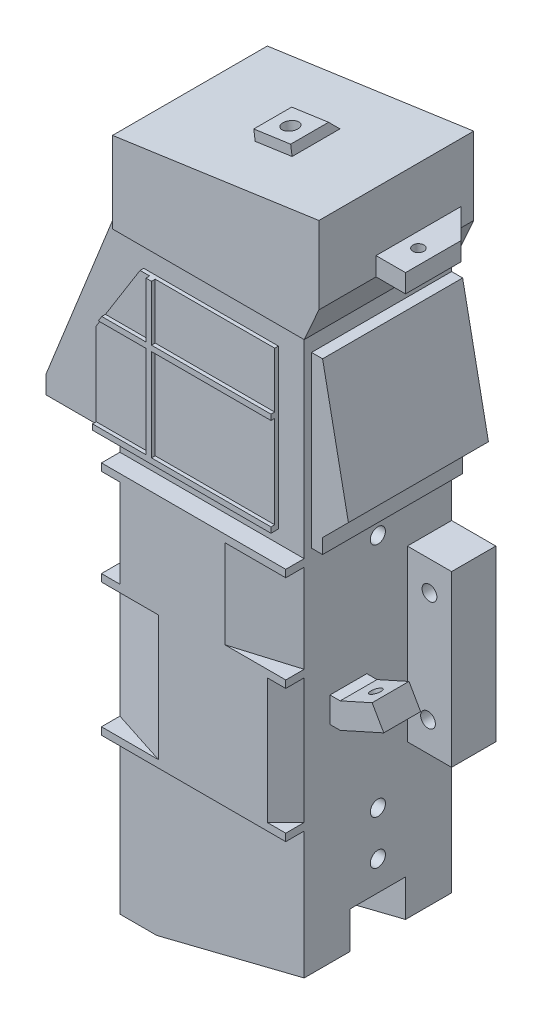
SolidWorks part; units mm, degrees
ref_plane "Alzado" through (0, 0, 0) normal (0, 0, 1) x (1, 0, 0)
ref_plane "Planta" through (0, 0, 0) normal (0, 1, 0) x (1, 0, 0)
ref_plane "Vista lateral" through (0, 0, 0) normal (1, 0, 0) x (0, 0, -1)
sketch "Croquis1" plane through (0, 0, 0) normal (0, 0, 1) x (1, 0, 0)
  line L1 (-25, -92) -> (25, -92)
  line L2 (-25, -92) -> (-25, 92)
  line L3 (-25, 92) -> (25, 92)
  line L4 (25, -92) -> (25, 92)
  line L5 (-25, -92) -> (25, 92) construction
  line L6 (-25, 92) -> (25, -92) construction
  point P0 (0, 0)
  dimension "D1" = 184
  dimension "D2" = 50
extrude "Saliente-Extruir1" add sketch "Croquis1" along normal blind 40
sketch "Croquis2" plane through (0, 0, 40) normal (0, 0, 1) x (1, 0, 0)
  line L0 (-25, -92) -> (-15, -92)
  line L1 (-25, -92) -> (25, -92) construction
  line L2 (-15, -92) -> (25, -82.0002)
  line L3 (25, -92) -> (25, 92) construction
  line L4 (25, -82.0002) -> (25, -92)
  line L5 (25, -92) -> (-15, -92)
  dimension "D1" = 10
  dimension "D2" = 41.231
extrude "Cortar-Extruir1" cut sketch "Croquis2" against normal blind 40 contours L2 L4 L5
sketch "Croquis3" plane through (0, 0, 40) normal (0, 0, 1) x (1, 0, 0)
  line L0 (25, -82.0002) -> (25, -40.5002)
  line L1 (25, -82.0002) -> (25, 92) construction
  line L2 (25, -40.5002) -> (17.2579, -40.5002)
  line L3 (25, -40.5002) -> (37, -40.5002)
  line L5 (23, 5.4998) -> (37, 5.4998)
  line L6 (37, -40.5002) -> (37, 5.4998)
  line L7 (17.2579, -40.5002) -> (17.2579, 5.4998)
  line L8 (17.2579, 5.4998) -> (23, 5.4998)
  circle A0 centre (30.6, -32.5002) radius 2
  circle A1 centre (31, -2.5002) radius 2
  line M8 (25, -82.0002) -> (25, 92)
  dimension "D4" = 4
  dimension "D7" = 8
  dimension "D1" = 41.5
  dimension "D2" = 12
  dimension "D3" = 46
  dimension "D5" = 6
  dimension "D6" = 30
extrude "Saliente-Extruir2" add sketch "Croquis3" against normal through all contours L3 L6 L5 A1 A0 M8 | L8 L7 L2 M8
sketch "Croquis4" plane through (0, 0, 40) normal (0, 0, 1) x (1, 0, 0)
  line L0 (25, 5.4998) -> (25, 17.9998)
  line L1 (25, 5.4998) -> (25, 92) construction
  line L2 (25, 17.9998) -> (28, 17.9998)
  line L3 (28, 17.9998) -> (28, 21.9998)
  line L4 (28, 21.9998) -> (34.9997, 28.9994)
  line L5 (34.9997, 28.9994) -> (27.9996, 63.9993)
  line L6 (27.9996, 63.9993) -> (25, 63.9993)
  line L7 (25, 63.9993) -> (25, 17.9998)
  line L8 (25, 63.9993) -> (25, 69.9993)
  line L9 (25, 69.9993) -> (27, 69.9993)
  line L10 (27, 69.9993) -> (31.0001, 78.9994)
  line L11 (31.0001, 78.9994) -> (42.3141, 78.9994)
  line L12 (42.3141, 78.9994) -> (42.3141, 83.9994)
  line L13 (42.3141, 83.9994) -> (31.0001, 83.9994)
  line L14 (25, 92) -> (31.0001, 92)
  line L15 (31.0001, 92) -> (31.0001, 83.9994)
  line L16 (25, 69.9993) -> (25, 92)
  dimension "D1" = 12.5
  dimension "D2" = 3
  dimension "D3" = 4
  dimension "D4" = 9.899
  dimension "D5" = 135
  dimension "D6" = 35.693
  dimension "D7" = 123.69
  dimension "D8" = 6
  dimension "D9" = 2
  dimension "D10" = 9.849
  dimension "D11" = 113.963
  dimension "D12" = 11.314
  dimension "D13" = 5
sketch "Croquis7" plane through (0, 0, 0) normal (0, 0, -1) x (-1, 0, 0)
  line L0 (-25, 17.9998) -> (-28, 17.9998)
  line L1 (-28, 17.9998) -> (-28, 21.9998)
  line L2 (-28, 21.9998) -> (-34.9997, 28.9994)
  line L3 (-34.9997, 28.9994) -> (-27.9996, 63.9993)
  line L4 (-27.9996, 63.9993) -> (-25, 63.9993)
  line L5 (-25, 63.9993) -> (-25, 17.9998)
extrude "Saliente-Extruir3" add sketch "Croquis7" against normal blind 38
sketch "Croquis8" plane through (0, 0, 0) normal (0, 0, -1) x (-1, 0, 0)
  line L0 (-25, 69.9993) -> (-27, 69.9993)
  line L1 (-27, 69.9993) -> (-31.0001, 78.9994)
  line L2 (-31.0001, 78.9994) -> (-42.3141, 78.9994)
  line L3 (-42.3141, 78.9994) -> (-42.3141, 83.9994)
  line L4 (-42.3141, 83.9994) -> (-31.0001, 83.9994)
  line L5 (-31.0001, 83.9994) -> (-31.0001, 92)
  line L6 (-31.0001, 92) -> (-25, 92)
  line L7 (-25, 92) -> (-25, 69.9993)
extrude "Saliente-Extruir4" add sketch "Croquis8" against normal through all
sketch "Croquis9" plane through (37, 0, 0) normal (1, 0, 0) x (0, 0, -1)
  line L0 (0, -40.5002) -> (-40, -40.5002) construction
  line L4 (-12, 5.4998) -> (-12, -40.5002)
  line L5 (-12, 5.4998) -> (-40, 5.4998)
  line L6 (-40, 5.4998) -> (-40, -40.5002)
  line L7 (-40, -40.5002) -> (-12, -40.5002)
extrude "Cortar-Extruir6" cut sketch "Croquis9" against normal blind 12
sketch "Croquis10" plane through (0, 78.9994, 0) normal (0, -1, 0) x (1, 0, 0)
  line L0 (31.0001, 40) -> (31.0001, 26.5)
  line L1 (31.0001, 40) -> (31.0001, 0) construction
  line L2 (31.0001, 26.5) -> (39.0001, 26.5)
  line L3 (39.0001, 26.5) -> (39.0001, 11.5)
  line L4 (39.0001, 11.5) -> (30.9999, 3.4998)
  line L6 (31.0001, 40) -> (42.3141, 40)
  line L7 (42.3141, 40) -> (42.3141, 0)
  line L9 (30.9999, 3.4998) -> (31.0001, 0)
  line L10 (31.0001, 0) -> (42.3141, 0)
  dimension "D1" = 13.5
  dimension "D2" = 8
  dimension "D3" = 15
  dimension "D4" = 135
  dimension "D5" = 11.314
extrude "Cortar-Extruir8" cut sketch "Croquis10" against normal blind 12
sketch "Croquis13" plane through (31.0001, 0, 0) normal (1, 0, 0) x (0, 0, -1)
  line L0 (0, 90.9994) -> (-3.4998, 90.9994)
  line L1 (-3.4998, 90.9994) -> (-3.4998, 78.9994)
  line L2 (-3.4998, 78.9994) -> (0, 78.9994)
  line L3 (0, 78.9994) -> (0, 90.9994)
extrude "Saliente-Extruir5" add sketch "Croquis13" against normal blind 12
sketch "Croquis14" plane through (0, 78.9994, 0) normal (0, -1, 0) x (1, 0, 0)
  line L0 (39.0001, 26.5) -> (39.0001, 11.5) construction
  line L1 (31.0001, 26.5) -> (39.0001, 26.5) construction
  circle A0 centre (35.0001, 19) radius 1.5
  dimension "D1" = 3
  dimension "D2" = 4
  dimension "D3" = 7.5
extrude "Cortar-Extruir9" cut sketch "Croquis14" against normal blind 12
sketch "Croquis16" plane through (25, 0, 0) normal (1, 0, 0) x (0, 0, -1)
  line L0 (0, -82.0002) -> (-40, -82.0002) construction
  line L1 (-33, -25.9192) -> (-23, -25.9192)
  line L2 (-33, -25.9192) -> (-33, -18.9912)
  line L3 (-33, -18.9912) -> (-23, -18.9912)
  line L4 (-23, -25.9192) -> (-23, -18.9912)
  line L5 (-40, -82.0002) -> (-40, 69.9993) construction
  dimension "D1" = 56.081
  dimension "D2" = 10
  dimension "D3" = 7
  dimension "D4" = 6.928
extrude "Saliente-Extruir6" add sketch "Croquis16" along normal blind 2.773
sketch3d "Croquis3D1"
  line L0 (27.773, -25.9192, 28) -> (39.597, -20.6034, 28)
  line L1 (27.773, -25.9192, 33) -> (27.773, -25.9192, 23) construction
  line L2 (27.773, -18.9912, 28) -> (36.4376, -15.0958, 28)
  line L3 (27.773, -18.9912, 23) -> (27.773, -18.9912, 33) construction
  line L4 (39.597, -20.6034, 28) -> (36.4376, -15.0958, 28)
  line L5 (27.773, -25.9192, 28) -> (27.773, -18.9912, 28)
  dimension "D1" = 12.964
  dimension "D2" = 9.5
extrude "Saliente-Extruir7" add sketch "Croquis3D1" along direction (0, 0, -1) on the side of the normal mid plane 10 contours L2 L4 L0 L5
sketch "Croquis19" plane through (14.363, -31.948, 0) normal (0.41, -0.9121, 0) x (0.9121, 0.41, 0)
  line L0 (27.6668, 23) -> (27.6668, 33) construction
  line L1 (14.7028, 23) -> (27.6668, 23) construction
  circle A0 centre (22.6668, 28) radius 1.5
  dimension "D1" = 3
  dimension "D3" = 5
  dimension "D2" = 5
extrude "Cortar-Extruir10" cut sketch "Croquis19" against normal blind 10
sketch "Croquis20" plane through (0, -92, 0) normal (0, -1, 0) x (1, 0, 0)
  line L0 (-15, 12.5) -> (-15, 27.5)
  line L1 (-15, 0) -> (-15, 40) construction
  line L2 (-15, 27.5) -> (25, 27.5)
  line L3 (25, 33) -> (25, 23) construction
  line L4 (25, 27.5) -> (25, 12.5)
  line L5 (25, 38) -> (25, 0) construction
  line L6 (25, 12.5) -> (-15, 12.5)
  line L7 (-15, 0) -> (25, 0) construction
  line L8 (-15, 40) -> (25, 40) construction
  point P5 (-15, 20)
  dimension "D1" = 12.5
  dimension "D2" = 12.5
extrude "Cortar-Extruir11" cut sketch "Croquis20" against normal blind 20
sketch "Croquis21" plane through (0, 0, 0) normal (0, 0, -1) x (-1, 0, 0)
  line L0 (25, 92) -> (25, 70) construction
  line L1 (25, 92) -> (25, -92) construction
  line L2 (25, 70) -> (27, 70)
  line L3 (25, -92) -> (25, 20) construction
  line L4 (25, 20) -> (45, 20)
  line L5 (45, 20) -> (45, 25)
  line L6 (27, 70) -> (45, 25)
  line L7 (25, 70) -> (25, 20)
  dimension "D1" = 22
  dimension "D2" = 2
  dimension "D3" = 112
  dimension "D4" = 20
  dimension "D5" = 5
extrude "Saliente-Extruir8" add sketch "Croquis21" against normal blind 40
sketch "Croquis22" plane through (0, 0, 40) normal (0, 0, 1) x (1, 0, 0)
  line L0 (31.0001, 92) -> (31.0001, 99.9994)
  line L2 (-25, 92) -> (31.0001, 99.9994)
  line L3 (-25, 92) -> (31.0001, 92)
  line L4 (31.0001, 92) -> (31.0001, 99.9994)
  line M4 (31.0001, 92) -> (-25, 92)
extrude "Saliente-Extruir9" add sketch "Croquis22" against normal blind 40 contours L2 L0 M4
sketch "Croquis23" plane through (0, 0, 40) normal (0, 0, 1) x (1, 0, 0)
  line L0 (-25, 70) -> (25, 69.9993)
  line L1 (25, 69.9993) -> (27, 69.9993)
  line L2 (27, 69.9993) -> (31.0001, 78.9994)
  line L3 (31.0001, 78.9994) -> (31.0001, 99.9994)
  line L4 (31.0001, 99.9994) -> (-25, 92)
  line L5 (-25, 92) -> (-25, 70)
extrude "Saliente-Extruir10" add sketch "Croquis23" along normal blind 2
sketch "Croquis25" plane through (0, 70, 0) normal (0, 1, 0) x (1, 0, 0)
  line L0 (-27, -40) -> (-27, -27.5)
  line L1 (-27, -40) -> (-27, 0) construction
  line L2 (-27, -27.5) -> (-45, -27.5)
  line L3 (-45, -40) -> (-45, 0) construction
  line L4 (-45, -27.5) -> (-45, -12.5)
  line L5 (-45, -12.5) -> (-27, -12.5)
  line L6 (-27, -12.5) -> (-27, -27.5)
  line L7 (-45, 0) -> (-27, 0) construction
  line M4 (-27, 0) -> (-27, -40)
  dimension "D1" = 12.5
  dimension "D2" = 12.5
extrude "Cortar-Extruir12" cut sketch "Croquis25" against normal blind 45 contours L5 L4 L2 M4
sketch "Croquis26" plane through (0, 25, 0) normal (0, 1, 0) x (1, 0, 0)
  line L0 (-45, -20) -> (-27, -20) construction
  line L1 (-45, -27.5) -> (-45, -12.5) construction
  line L2 (-27, -12.5) -> (-27, -27.5) construction
  circle A0 centre (-36, -20) radius 1.6
  dimension "D1" = 3.2
extrude "Cortar-Extruir13" cut sketch "Croquis26" against normal blind 45
sketch "Croquis28" plane through (0, 0, 40) normal (0, 0, 1) x (1, 0, 0)
  line L0 (-30.431, 20) -> (18, 20)
  line L2 (-25, -92) -> (-15, -92) construction
  line L3 (25, -82.0002) -> (25, 69.9993) construction
  line L4 (18, 20) -> (18, 63)
  line L5 (18, 63) -> (-18.529, 63)
  line L6 (-30.431, 20) -> (-30.431, 43.969)
  line L7 (-30.431, 43.969) -> (-18.529, 63)
  dimension "D1" = 112
  dimension "D2" = 7
  dimension "D3" = 48.431
  dimension "D4" = 43
  dimension "D5" = 36.529
  dimension "D6" = 23.969
extrude "Saliente-Extruir11" add sketch "Croquis28" along normal blind 1
sketch "Croquis29" plane through (0, 0, 41) normal (0, 0, 1) x (1, 0, 0)
  line L0 (18, 20) -> (18, 21.5)
  line L1 (-18.529, 63) -> (-15.919, 63)
  line L2 (18, 20) -> (18, 63) construction
  line L3 (18, 21.5) -> (-30.431, 21.5)
  line L4 (-30.431, 43.969) -> (-30.431, 20) construction
  line L5 (-30.431, 21.5) -> (-30.431, 20)
  line L6 (-30.431, 20) -> (18, 20)
  line L7 (-30.431, 21.5) -> (-22.6197, 21.5)
  line L8 (18, 63) -> (-18.529, 63) construction
  line L9 (-15.919, 63) -> (-15.919, 21.5)
  line L10 (-15.919, 21.5) -> (-14.419, 21.5)
  line L11 (-14.419, 21.5) -> (-14.419, 63)
  line L12 (18, 63) -> (-18.529, 63) construction
  line L13 (-14.419, 63) -> (-15.919, 63)
  line L14 (-15.919, 63) -> (-15.919, 47.99)
  line L15 (-15.919, 47.99) -> (18, 47.99)
  line L16 (18, 47.99) -> (18, 46.49)
  line L17 (18, 20) -> (18, 63) construction
  line L18 (18, 46.49) -> (-28.8544, 46.49)
  line L19 (-18.529, 63) -> (-30.431, 43.969) construction
  line L20 (-15.919, 47.99) -> (-27.9163, 47.99)
  line L21 (-18.529, 63) -> (-30.431, 43.969) construction
  line L22 (-27.9163, 47.99) -> (-28.8544, 46.49)
  dimension "D1" = 1.5
  dimension "D2" = 2.61
  dimension "D3" = 1.5
  dimension "D4" = 15.01
  dimension "D5" = 1.5
extrude "Saliente-Extruir12" add sketch "Croquis29" along normal blind 1 contours L9 L10 L11 L13 | L15 L16 L18 L22 L20 | L5 L6 L0 L3
sketch "Croquis30" plane through (0, 0, 40) normal (0, 0, 1) x (1, 0, 0)
  line L0 (25, 16.538) -> (-25, 16.538)
  line L1 (-25, 20) -> (18, 20) construction
  line L2 (25, -82.0002) -> (25, 69.9993) construction
  line L3 (-25, 20) -> (-25, -92) construction
  line L4 (-25, 16.538) -> (-25, 14.538)
  line L5 (-25, 14.538) -> (25, 14.538)
  line L6 (25, 14.538) -> (25, 16.538)
  dimension "D1" = 3.462
  dimension "D2" = 2
extrude "Saliente-Extruir13" add sketch "Croquis30" along normal blind 5 contours L6 L0 L4 L5
sketch "Croquis31" plane through (0, 14.538, 0) normal (0, -1, 0) x (1, 0, 0)
  line L0 (-25, 40) -> (-20.0001, 45)
  line L1 (-25, 45) -> (25, 45) construction
  line L2 (-20.0001, 45) -> (8.4619, 45)
  line L3 (8.4619, 45) -> (25, 40)
  line L4 (25, 40) -> (-25, 40)
  dimension "D1" = 7.071
  dimension "D2" = 28.462
extrude "Saliente-Extruir14" add sketch "Croquis31" along normal blind 24
sketch "Croquis32" plane through (0, 0, 45) normal (0, 0, 1) x (1, 0, 0)
  line L0 (-20.0001, 14.538) -> (-25, 7.4672)
  line L1 (-25, 14.538) -> (-25, -9.462) construction
  line L2 (-25, 7.4672) -> (-25, 14.538)
  line L3 (-25, 14.538) -> (-20.0001, 14.538)
  dimension "D1" = 8.66
extrude "Cortar-Extruir14" cut sketch "Croquis32" against normal blind 5
sketch "Croquis33" plane through (0, -9.462, 0) normal (0, -1, 0) x (1, 0, 0)
  line L0 (-25, 40) -> (-25, 45)
  line L1 (-25, 45) -> (25, 45)
  line L2 (25, 45) -> (25, 40)
  line L3 (25, 40) -> (-25, 40)
extrude "Saliente-Extruir15" add sketch "Croquis33" along normal blind 2
sketch "Croquis34" plane through (0, -11.462, 0) normal (0, -1, 0) x (1, 0, 0)
  line L0 (-25, 40) -> (-9.5194, 45)
  line L1 (25, 45) -> (-25, 45) construction
  line L2 (-9.5194, 45) -> (19.9996, 45)
  line L3 (19.9996, 45) -> (25, 40)
  line L4 (25, 40) -> (-25, 40)
  dimension "D1" = 16.268
  dimension "D2" = 29.519
extrude "Saliente-Extruir16" add sketch "Croquis34" along normal blind 34
sketch "Croquis35" plane through (0, -45.462, 0) normal (0, -1, 0) x (1, 0, 0)
  line L0 (-25, 40) -> (-25, 45)
  line L1 (-25, 45) -> (25, 45)
  line L2 (25, 45) -> (25, 40)
  line L3 (25, 40) -> (-25, 40)
extrude "Saliente-Extruir17" add sketch "Croquis35" along normal blind 2
sketch "Croquis36" plane through (-15, 0, 0) normal (1, 0, 0) x (0, 0, -1)
  line L0 (-20, -92) -> (-20, -72) construction
  line L1 (-27.5, -92) -> (-12.5, -92) construction
  line L2 (-27.5, -72) -> (-12.5, -72) construction
  circle A0 centre (-20, -82) radius 1.6
  dimension "D1" = 3.2
extrude "Cortar-Extruir15" cut sketch "Croquis36" against normal through all
sketch "Croquis37" plane through (25, 0, 0) normal (1, 0, 0) x (0, 0, -1)
  line L0 (-20, -72) -> (-20, -64) construction
  line L1 (-12.5, -72) -> (-27.5, -72) construction
  circle A0 centre (-20, -64) radius 2.05
  circle A1 centre (-20, -52) radius 2.05
  circle A2 centre (-20, 12) radius 2.05
  dimension "D1" = 4.1
  dimension "D2" = 12
  dimension "D3" = 8
  dimension "D4" = 64
extrude "Cortar-Extruir16" cut sketch "Croquis37" against normal blind 6
sketch "Croquis38" plane through (0, 0, 0) normal (0, 0, -1) x (-1, 0, 0)
  line L0 (25, 92) -> (25, 70) construction
  line L1 (25, 92) -> (-31.0001, 99.9994) construction
  circle A0 centre (-6.684, 79.6193) radius 2.05
  circle A1 centre (2.316, 79.6193) radius 2.05
  dimension "D1" = 4.1
  dimension "D4" = 15.464
  dimension "D2" = 9
  dimension "D3" = 22.684
extrude "Cortar-Extruir17" cut sketch "Croquis38" against normal blind 6
sketch "Croquis39" plane through (-13.3789, 93.66, 0) normal (-0.1414, 0.99, 0) x (0.99, 0.1414, 0)
  line L0 (44.8295, -21) -> (22.8295, -21)
  line L2 (44.8295, 0) -> (44.8295, -42) construction
  line L3 (22.8295, -27.5) -> (22.8295, -14.5)
  line L4 (22.8295, -14.5) -> (12.7205, -14.5)
  line L5 (12.7205, -14.5) -> (12.7205, -27.5)
  line L6 (12.7205, -27.5) -> (22.8295, -27.5)
  point P7 (22.8295, -21)
  dimension "D1" = 22
  dimension "D2" = 13
  dimension "D3" = 10.109
extrude "Saliente-Extruir18" add sketch "Croquis39" along normal blind 2.741 contours L5 L6 L3 L4
sketch "Croquis40" plane through (12.5927, 1.7988, 0) normal (-0.99, -0.1414, 0) x (0, 0, 1)
  line L3 (14.5, 94.6108) -> (15.746, 95.8698)
  line L6 (14.5, 97.3518) -> (27.5, 97.3518) construction
  line L7 (15.746, 95.8698) -> (17.211, 97.3518)
  line L8 (17.211, 97.3518) -> (14.5, 97.3518)
  line L9 (14.5, 97.3518) -> (14.5, 94.6108)
extrude "Cortar-Extruir18" cut sketch "Croquis40" against normal through all contours L8 L9 L3 L7
sketch "Croquis42" plane through (-13.7665, 96.3735, 0) normal (-0.1414, 0.99, 0) x (0.99, 0.1414, 0)
  line L0 (12.7205, -27.5) -> (22.8295, -27.5) construction
  line L1 (12.7205, -17.211) -> (12.7205, -27.5) construction
  circle A0 centre (17.7205, -22.5) radius 2.05
  dimension "D1" = 4.1
  dimension "D2" = 5
  dimension "D3" = 5
extrude "Cortar-Extruir19" cut sketch "Croquis42" against normal blind 6
